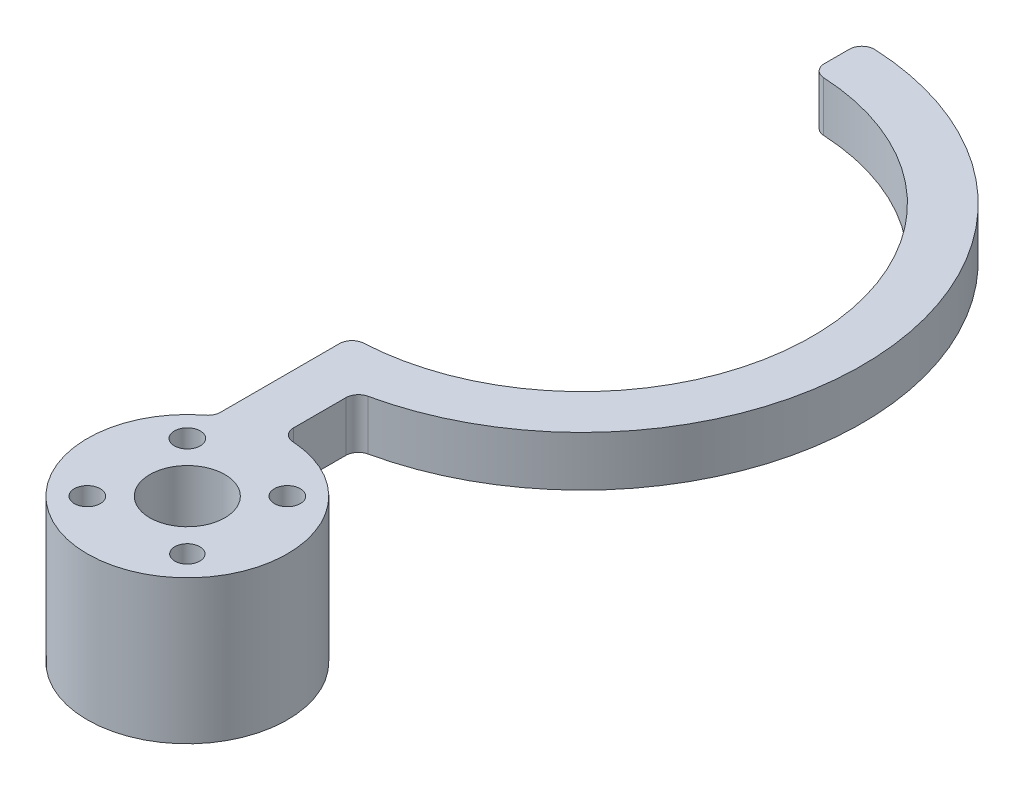
SolidWorks part; units mm, degrees
ref_plane "Front Plane" through (0, 0, 0) normal (0, 0, 1) x (1, 0, 0)
ref_plane "Top Plane" through (0, 0, 0) normal (0, 1, 0) x (1, 0, 0)
ref_plane "Right Plane" through (0, 0, 0) normal (1, 0, 0) x (0, 0, -1)
sketch "Sketch1" plane through (0, 0, 0) normal (0, 1, 0) x (1, 0, 0)
  line L0 (0, 44.83) -> (0, 36.83)
  line L1 (0, -36.83) -> (0, -46.83)
  line L2 (0, -46.83) -> (0, -58.83)
  line L3 (8, -44.1104) -> (8, -56.1104)
  line L8 (16.967, -80.0812) -> (0.967, -80.0812) construction
  line L13 (16.967, -80.0812) -> (16.967, -64.0812) construction
  line L21 (16.967, -64.0812) -> (0.967, -64.0812) construction
  line L22 (0.967, -80.0812) -> (0.967, -64.0812) construction
  line L23 (16.967, -80.0812) -> (0.967, -64.0812) construction
  line L24 (16.967, -64.0812) -> (0.967, -80.0812) construction
  arc A0 (0, -36.83) -> (0, 36.83) centre (0, 0) ccw
  arc A1 (8, -44.1104) -> (0, 44.83) centre (0, 0) ccw
  arc A7 (0, -58.83) -> (23.0776, -79.6236) centre (8.967, -72.0812) ccw
  circle A8 centre (0.967, -64.0812) radius 2.075
  circle A9 centre (16.967, -64.0812) radius 2.075
  circle A10 centre (16.967, -80.0812) radius 2.075
  circle A11 centre (0.967, -80.0812) radius 2.075
  arc A12 (0, -58.83) -> (8, -56.1104) centre (8.967, -72.0812) ccw
  circle A13 centre (8.967, -72.0812) radius 6.0032
  dimension "D1" = 73.66
  dimension "D8" = 4.15
  dimension "D6" = 16
  dimension "D2" = 8
  dimension "D3" = 8
  dimension "D4" = 12
  dimension "D9" = 10
  dimension "D7" = 16
  dimension "D5" = 12
extrude "Boss-Extrude2" add sketch "Sketch1" along normal blind 8 contours A7 A12 L3 A1 L0 A0 L1 L2 A8 A9 A10 A11
fillet "Fillet1" radius 2 6 edges at (0, 4, -36.83) (0, 4, -44.83) (8, 4, 56.1104) (8, 4, 44.1104) (0, 4, 58.83) (0, 4, 36.83)
sketch "Sketch2" plane through (0, 8, 0) normal (0, 1, 0) x (1, 0, 0)
  circle A0 centre (8.967, -72.0812) radius 16
  circle A1 centre (8.967, -72.0812) radius 6.0032
  circle A2 centre (16.967, -80.0812) radius 2.0015
  circle A3 centre (16.967, -64.0812) radius 2.075
  circle A4 centre (0.967, -64.0812) radius 2.075
  circle A5 centre (0.967, -80.0812) radius 2.075
extrude "Boss-Extrude3" add sketch "Sketch2" against normal blind 23
equation "\"innerSmall\"= 2.9in"
equation "\"thick\"= 8mm"
equation "\"D1@Sketch1\"=\"innerSmall\""
equation "\"D2@Sketch1\"=\"thick\""
equation "\"D3@Sketch1\"=\"thick\""
equation "\"D7@Sketch1\"=16mm"
